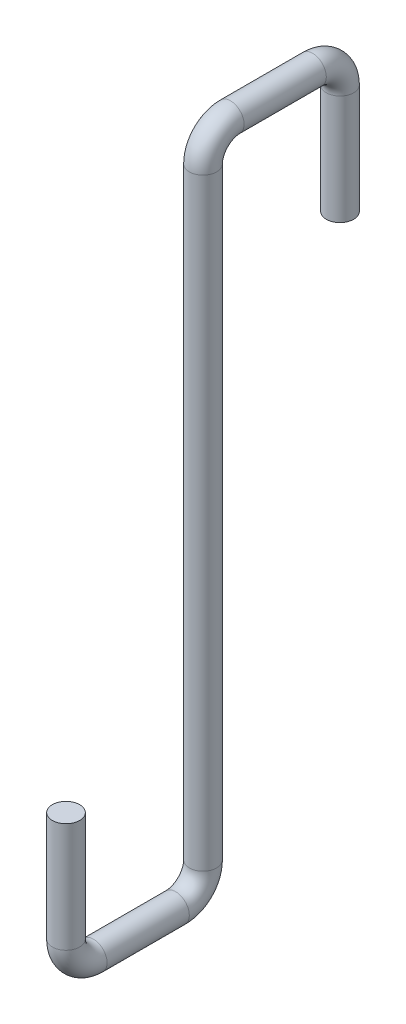
SolidWorks part; units mm, degrees
ref_plane "Front Plane" through (0, 0, 0) normal (0, 0, 1) x (1, 0, 0)
ref_plane "Top Plane" through (0, 0, 0) normal (0, 1, 0) x (1, 0, 0)
ref_plane "Right Plane" through (0, 0, 0) normal (1, 0, 0) x (0, 0, -1)
sketch3d "3DSketch1"
  line L0 (0, 0, -1.5) -> (0, 0, 1.5)
  line L1 (0, -1, 2.5) -> (0, -23, 2.5)
  line L2 (0, -24, 3.5) -> (0, -24, 6.5)
  line L3 (0, -1, -2.5) -> (0, -5, -2.5)
  line L4 (0, -23, 7.5) -> (0, -19, 7.5)
  arc A0 (0, -24, 6.5) -> (0, -23, 7.5) centre (0, -23, 6.5) ccw
  arc A1 (0, -23, 2.5) -> (0, -24, 3.5) centre (0, -23, 3.5) ccw
  arc A2 (0, 0, 1.5) -> (0, -1, 2.5) centre (0, -1, 1.5) ccw
  arc A3 (0, 0, -1.5) -> (0, -1, -2.5) centre (0, -1, -1.5) ccw
  point P9 (0, -24, 7.5)
  point P10 (-1, -23, 6.5)
  point P13 (0, -24, 2.5)
  point P17 (-1, -23, 3.5)
  point P20 (0, 0, 2.5)
  point P21 (1, -1, 1.5)
  point P24 (0, 0, -2.5)
  point P25 (-1, -1, -1.5)
  dimension "D2" = 1
  dimension "D1" = 24
  dimension "D3" = 5
  dimension "D4" = 5
sweep "Sweep1" add path "3DSketch1" circular profile diameter 1 parameters "D3"=1
